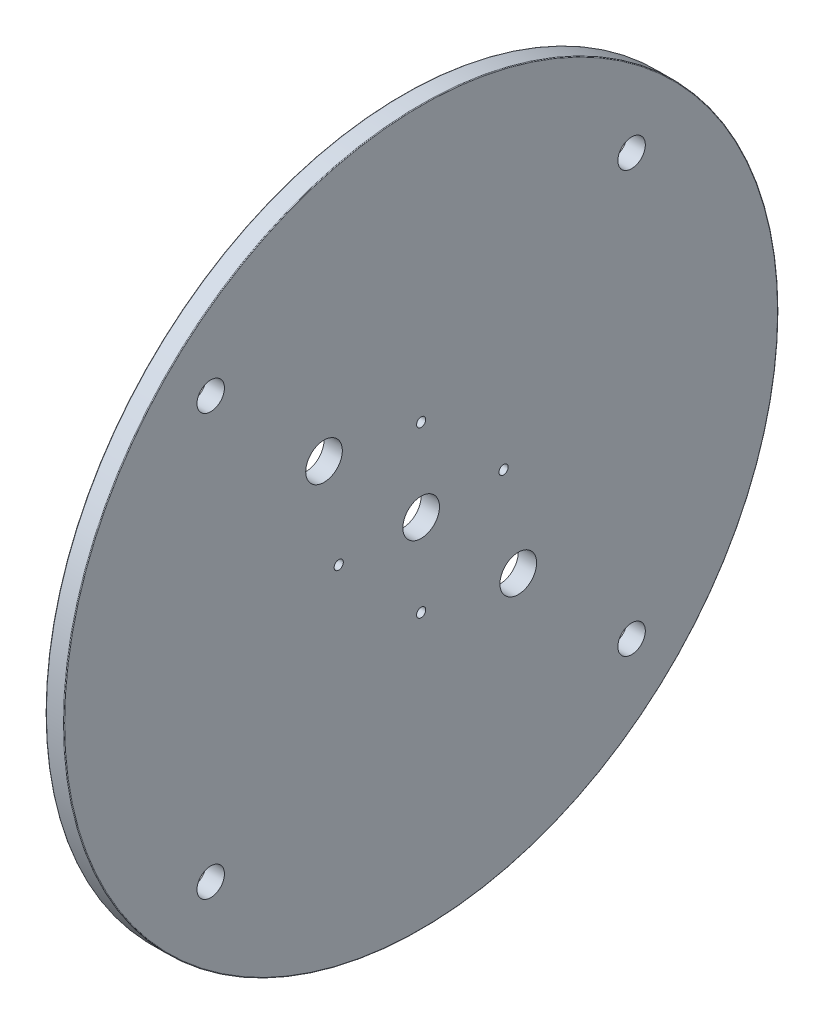
SolidWorks part; units mm, degrees
material "1060 合金"
ref_plane "前视基准面" through (0, 0, 0) normal (0, 0, 1) x (1, 0, 0)
ref_plane "上视基准面" through (0, 0, 0) normal (0, 1, 0) x (1, 0, 0)
ref_plane "右视基准面" through (0, 0, 0) normal (1, 0, 0) x (0, 0, -1)
sketch "草图1" plane through (0, 0, 0) normal (1, 0, 0) x (0, 0, -1)
  circle A0 centre (0, 0) radius 156
extrude "凸台-拉伸1" add sketch "草图1" along normal blind 8
sketch "草图4" plane through (8, 0, 0) normal (1, 0, 0) x (0, 0, -1)
  circle A1 centre (91.9239, 91.9239) radius 6
extrude "切除-拉伸3" cut sketch "草图4" against normal blind 10
pattern_circular "阵列(圆周)2" count 4 over 360 about axis through (0, 0, 0) along (1, 0, 0) of "切除-拉伸3"
fillet "圆角1" radius 0.3 2 edges at (0, 0, -156) (8, 0, -156)
sketch "草图7" plane through (8, 0, 0) normal (1, 0, 0) x (0, 0, -1)
  circle A4 centre (-56.5685, 56.5685) radius 4
extrude "切除-拉伸6" [suppressed] cut sketch "草图7" against normal blind 10
sketch "草图8" plane through (8, 0, 0) normal (1, 0, 0) x (0, 0, -1)
  circle A3 centre (42.4264, -42.4264) radius 8
extrude "切除-拉伸7" cut sketch "草图8" against normal blind 10
pattern_circular "阵列(圆周)3" count 2 over 360 about axis through (0, 0, 0) along (1, 0, 0) of "切除-拉伸7"
sketch "草图9" plane through (8, 0, 0) normal (1, 0, 0) x (0, 0, -1)
  circle A0 centre (0, 0) radius 8
extrude "切除-拉伸8" cut sketch "草图9" against normal blind 10
sketch "草图10" plane through (8, 0, 0) normal (1, 0, 0) x (0, 0, -1)
  circle A0 centre (36, 0) radius 2
  point P0 (0, 0)
  point P4 (0, 0)
extrude "切除-拉伸9" cut sketch "草图10" against normal blind 10 contours A0
pattern_circular "阵列(圆周)5" count 4 over 360 about axis through (0, 0, 0) along (1, 0, 0) of "切除-拉伸9"
